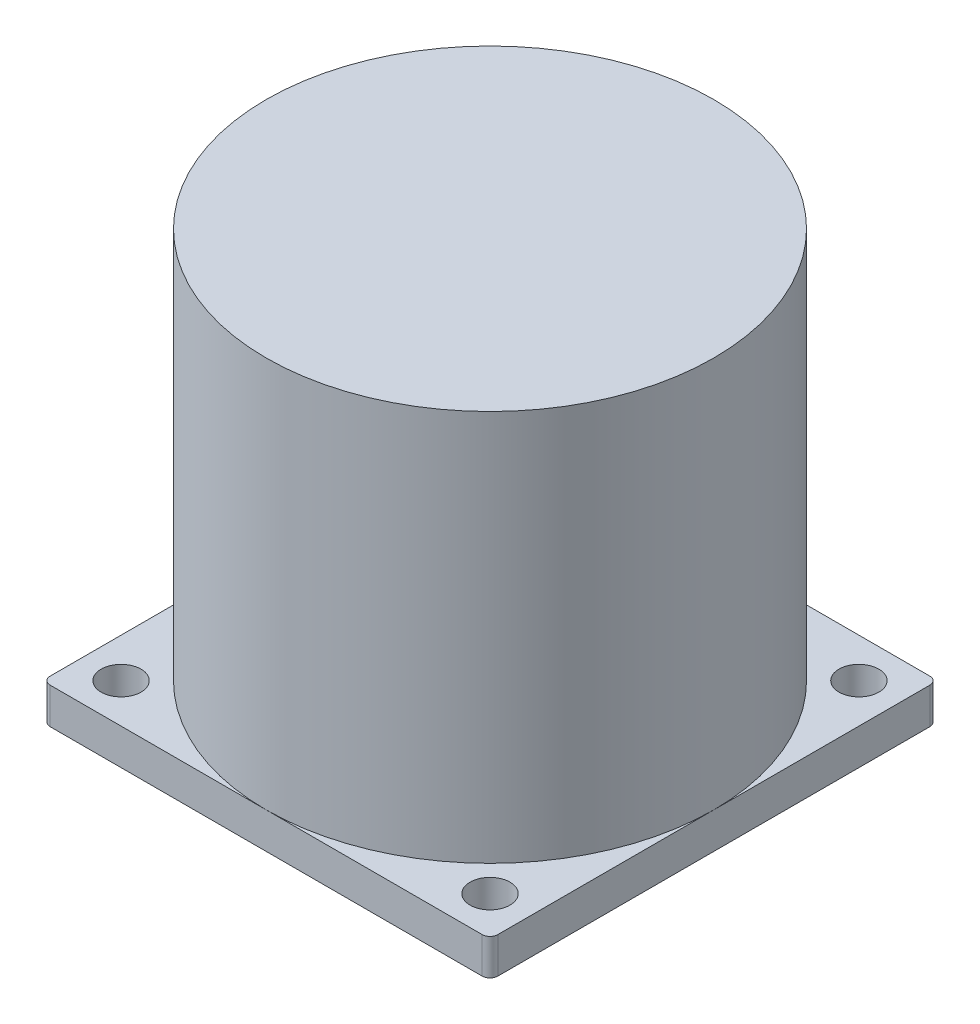
SolidWorks part; units mm, degrees
ref_plane "Спереди" through (0, 0, 0) normal (0, 0, 1) x (1, 0, 0)
ref_plane "Сверху" through (0, 0, 0) normal (0, 1, 0) x (1, 0, 0)
ref_plane "Справа" through (0, 0, 0) normal (1, 0, 0) x (0, 0, -1)
ref_plane "Плоскость4" through (0, -4.6, 0) normal (0, -1, 0) x (1, 0, 0)
sketch "Эскиз1" plane through (0, -4.6, 0) normal (0, -1, 0) x (1, 0, 0)
  line L0 (-28.6, 28.6) -> (-28.6, -28.6)
  line L1 (-28.6, -28.6) -> (28.6, -28.6)
  line L2 (28.6, -28.6) -> (28.6, 28.6)
  line L3 (28.6, 28.6) -> (-28.6, 28.6)
extrude "Бобышка-Вытянуть1" add sketch "Эскиз1" against normal blind 4.6
sketch "Эскиз2" plane through (0, 0, 0) normal (0, 0, 1) x (1, 0, 0)
  line L0 (28.6, 50) -> (0, 50)
  line L1 (0, 50) -> (0, 0)
  line L2 (0, 0) -> (28.6, 0)
  line L3 (28.6, 0) -> (28.6, 50)
  line L4 (0, 50) -> (0, 0) construction
revolve "Повернуть1" add sketch "Эскиз2" angle 360 about L4
ref_plane "Плоскость5" through (0, 0, 0) normal (0, 0, -1) x (-1, 0, 0)
sketch "Эскиз3" plane through (0, 0, 0) normal (0, 0, -1) x (-1, 0, 0)
  line L0 (-3.175, -25.2) -> (0, -25.2)
  line L1 (0, -25.2) -> (0, -4.6)
  line L2 (0, -4.6) -> (-19.05, -4.6)
  line L3 (-19.05, -4.6) -> (-19.05, -6.2)
  line L4 (-19.05, -6.2) -> (-3.175, -6.2)
  line L5 (-3.175, -6.2) -> (-3.175, -25.2)
  line L6 (0, -25.2) -> (0, -4.6) construction
revolve "Повернуть2" add sketch "Эскиз3" angle 360 about L6
hole_wizard "Диаметр отверстия Ø5.1 (5.1)1" positions "Эскиз5" profile "Эскиз4" hole size "Ø5.1" standard "Ansi Metric"
sketch "Эскиз5" plane through (0, -4.6, 0) normal (0, -1, 0) x (-1, 0, 0)
  point P0 (23.57, 23.57)
  point P1 (23.57, -23.57)
  point P2 (-23.57, -23.57)
  point P3 (-23.57, 23.57)
sketch "Эскиз4" plane through (-23.57, -4.6, -23.57) normal (1, 0, 0) x (0, 0, -1)
  line L0 (0, 0) -> (0, 54.6)
  line L1 (0, 54.6) -> (2.55, 54.6)
  line L2 (2.55, 54.6) -> (2.55, 0)
  line L5 (2.55, 0) -> (0, 0)
  line L11 (0, -6.35) -> (0, 107.95) construction
  dimension "Диаметр сквозного отверстия" = 5.1
  dimension "Глубина сквозного отверстия" = 54.6
fillet "Скругление1" radius 1 4 edges at (-28.6, -2.3, -28.6) (28.6, -2.3, -28.6) (-28.6, -2.3, 28.6) (28.6, -2.3, 28.6)
